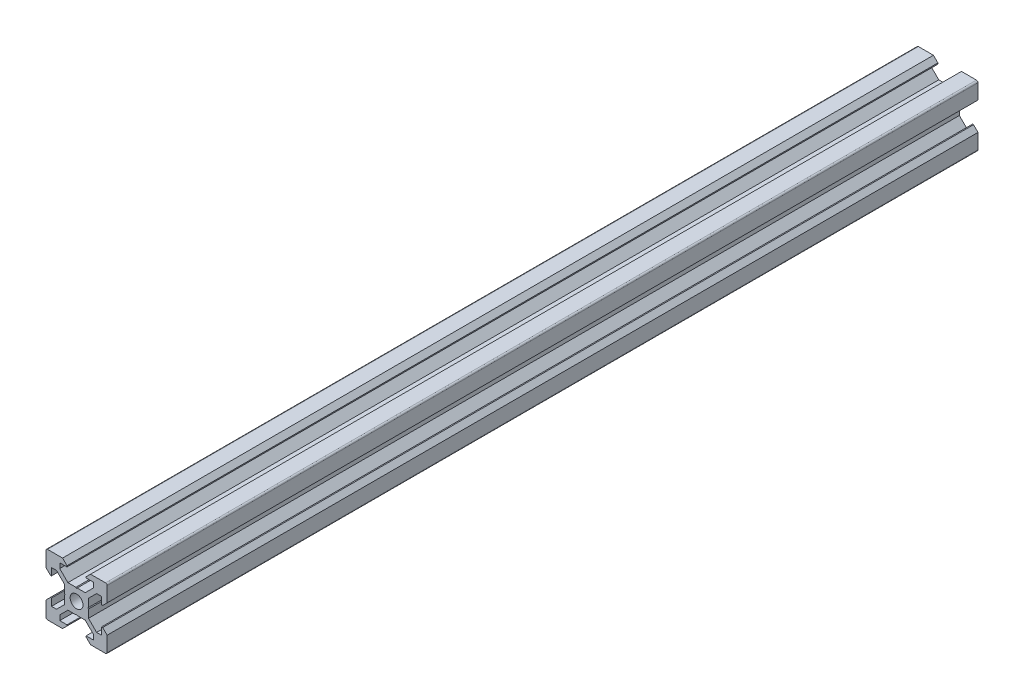
SolidWorks part; units mm, degrees
ref_plane "Plano frontal" through (0, 0, 0) normal (0, 0, 1) x (1, 0, 0)
ref_plane "Plano superior" through (0, 0, 0) normal (0, 1, 0) x (1, 0, 0)
ref_plane "Plano direito" through (0, 0, 0) normal (1, 0, 0) x (0, 0, -1)
sketch "Esboço1" plane through (0, 0, 0) normal (0, 0, 1) x (1, 0, 0)
  line L0 (3.9, -0.21) -> (3.69, 0)
  line L1 (3.69, 0) -> (3.9, 0.21)
  line L2 (3.9, 0.21) -> (3.9, 2.8393)
  line L3 (3.9, 2.8393) -> (6.5607, 5.5)
  line L4 (6.5607, 5.5) -> (8.2, 5.5)
  line L5 (8.2, 5.5) -> (8.2, 3.125)
  line L6 (8.2, 3.125) -> (8.545, 3.125)
  line L7 (8.545, 3.125) -> (10, 4.58)
  line L8 (10, 4.58) -> (10, 9.5)
  line L9 (9.5, 10) -> (4.58, 10)
  line L10 (4.58, 10) -> (3.125, 8.545)
  line L11 (3.125, 8.545) -> (3.125, 8.2)
  line L12 (3.125, 8.2) -> (5.5, 8.2)
  line L13 (5.5, 8.2) -> (5.5, 6.5607)
  line L14 (5.5, 6.5607) -> (2.8393, 3.9)
  line L15 (2.8393, 3.9) -> (0.21, 3.9)
  line L16 (0.21, 3.9) -> (0, 3.69)
  line L17 (0, 3.69) -> (-0.21, 3.9)
  line L18 (-0.21, 3.9) -> (-2.8393, 3.9)
  line L19 (-2.8393, 3.9) -> (-5.5, 6.5607)
  line L20 (-5.5, 6.5607) -> (-5.5, 8.2)
  line L21 (-5.5, 8.2) -> (-3.125, 8.2)
  line L22 (-3.125, 8.2) -> (-3.125, 8.545)
  line L23 (-3.125, 8.545) -> (-4.58, 10)
  line L24 (-4.58, 10) -> (-9.5, 10)
  line L25 (-10, 9.5) -> (-10, 4.58)
  line L26 (-10, 4.58) -> (-8.545, 3.125)
  line L27 (-8.545, 3.125) -> (-8.2, 3.125)
  line L28 (-8.2, 3.125) -> (-8.2, 5.5)
  line L29 (-8.2, 5.5) -> (-6.5607, 5.5)
  line L30 (-6.5607, 5.5) -> (-3.9, 2.8393)
  line L31 (-3.9, 2.8393) -> (-3.9, 0.21)
  line L32 (-3.9, 0.21) -> (-3.69, 0)
  line L33 (-3.69, 0) -> (-3.9, -0.21)
  line L34 (-3.9, -0.21) -> (-3.9, -2.8393)
  line L35 (-3.9, -2.8393) -> (-6.5607, -5.5)
  line L36 (-6.5607, -5.5) -> (-8.2, -5.5)
  line L37 (-8.2, -5.5) -> (-8.2, -3.125)
  line L38 (-8.2, -3.125) -> (-8.545, -3.125)
  line L39 (-8.545, -3.125) -> (-10, -4.58)
  line L40 (-10, -4.58) -> (-10, -9.5)
  line L41 (-9.5, -10) -> (-4.58, -10)
  line L42 (-4.58, -10) -> (-3.125, -8.545)
  line L43 (-3.125, -8.545) -> (-3.125, -8.2)
  line L44 (-3.125, -8.2) -> (-5.5, -8.2)
  line L45 (-5.5, -8.2) -> (-5.5, -6.5607)
  line L46 (-5.5, -6.5607) -> (-2.8393, -3.9)
  line L47 (-2.8393, -3.9) -> (-0.21, -3.9)
  line L48 (-0.21, -3.9) -> (0, -3.69)
  line L49 (0, -3.69) -> (0.21, -3.9)
  line L50 (0.21, -3.9) -> (2.8393, -3.9)
  line L51 (2.8393, -3.9) -> (5.5, -6.5607)
  line L52 (5.5, -6.5607) -> (5.5, -8.2)
  line L53 (5.5, -8.2) -> (3.125, -8.2)
  line L54 (3.125, -8.2) -> (3.125, -8.545)
  line L55 (3.125, -8.545) -> (4.58, -10)
  line L56 (4.58, -10) -> (9.5, -10)
  line L57 (10, -9.5) -> (10, -4.58)
  line L58 (10, -4.58) -> (8.545, -3.125)
  line L59 (8.545, -3.125) -> (8.2, -3.125)
  line L60 (8.2, -3.125) -> (8.2, -5.5)
  line L61 (8.2, -5.5) -> (6.5607, -5.5)
  line L62 (6.5607, -5.5) -> (3.9, -2.8393)
  line L63 (3.9, -2.8393) -> (3.9, -0.21)
  circle A0 centre (0, 0) radius 2.1
  arc A1 (10, 9.5) -> (9.5, 10) centre (9.5, 9.5) ccw
  arc A2 (-9.5, 10) -> (-10, 9.5) centre (-9.5, 9.5) ccw
  arc A3 (-10, -9.5) -> (-9.5, -10) centre (-9.5, -9.5) ccw
  arc A4 (9.5, -10) -> (10, -9.5) centre (9.5, -9.5) ccw
extrude "Ressalto-extrusão1" add sketch "Esboço1" along normal blind 285
ref_plane "Plano1" through (0, 0, 0) normal (0, 1, 0) x (1, 0, 0)
ref_plane "Plano2" through (0, 0, 0) normal (1, 0, 0) x (0, 0, -1)
